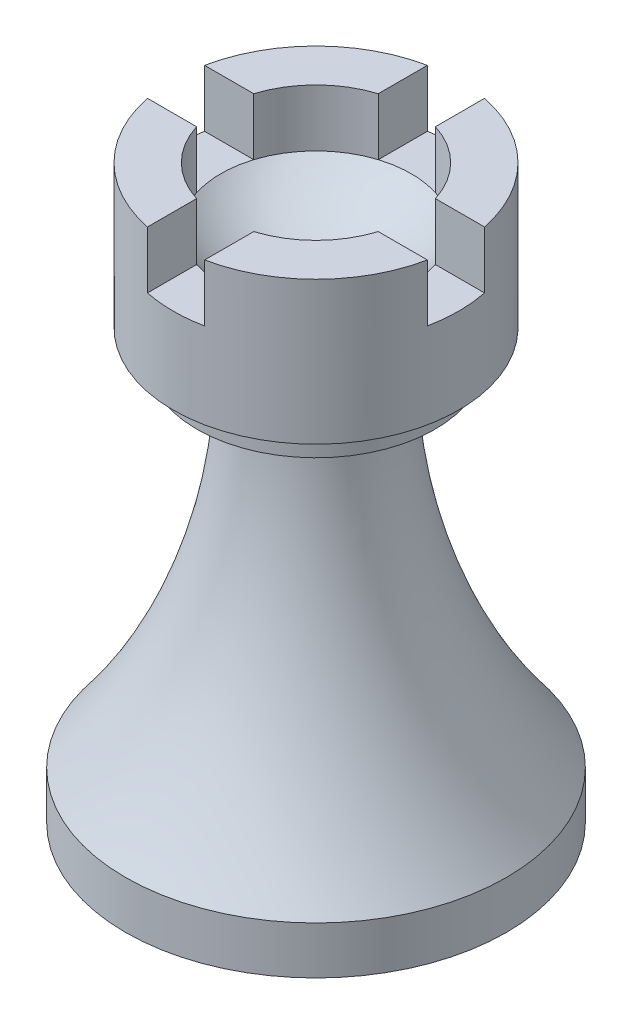
SolidWorks part; units mm, degrees
ref_plane "Front Plane" through (0, 0, 0) normal (0, 0, 1) x (1, 0, 0)
ref_plane "Top Plane" through (0, 0, 0) normal (0, 1, 0) x (1, 0, 0)
ref_plane "Right Plane" through (0, 0, 0) normal (1, 0, 0) x (0, 0, -1)
sketch "Sketch1" plane through (0, 0, 0) normal (0, 0, 1) x (1, 0, 0)
  line L0 (0, 46.6223) -> (0, -55.7864) construction
  line L2 (20, -37) -> (20, -42)
  line L3 (20, -42) -> (0, -42)
  line L4 (7.5, 0) -> (12.5, 0)
  line L5 (12.5, 0) -> (12.5, 3)
  line L6 (12.5, 3) -> (15, 3)
  line L7 (15, 3) -> (15, 18)
  line L8 (15, 18) -> (10, 18)
  line L9 (0, 0) -> (0, 8)
  line L10 (10, 12) -> (10, 18)
  line L11 (10, 3) -> (10, 18) construction
  line L12 (0, 0) -> (0, -42)
  arc A0 (0, 8) -> (10, 12) centre (-0.5956, 23.9889) ccw
  arc A1 (20, -37) -> (7.5, 0) centre (67.499, -0.3415) cw
  point P12 (7.5, 0)
  point P19 (10, 12)
  dimension "D8" = 60
  dimension "D2" = 5
  dimension "D3" = 20
  dimension "D4" = 7.5
  dimension "D5" = 12.5
  dimension "D6" = 3
  dimension "D7" = 15
  dimension "D9" = 10
  dimension "D11" = 6
revolve "Revolve1" add sketch "Sketch1" angle 360 about L0
fillet "Fillet1" radius 2 1 edges at (0, 0, 7.5)
sketch "Sketch2" plane through (0, 0, 0) normal (0, 0, 1) x (1, 0, 0)
  line L0 (10, 18) -> (-10, 18) construction
  line L1 (-3, 24) -> (3, 24)
  line L2 (-3, 24) -> (-3, 12)
  line L3 (-3, 12) -> (3, 12)
  line L4 (3, 24) -> (3, 12)
  line L5 (-3, 24) -> (3, 12) construction
  line L6 (-3, 12) -> (3, 24) construction
  point P0 (0, 18)
  dimension "D1" = 6
  dimension "D2" = 12
extrude "Cut-Extrude1" cut sketch "Sketch2" against normal up to next
pattern_circular "CirPattern1" count 4 over 360 about axis through (0, 0, 0) along (0, 1, 0) of "Cut-Extrude1"
scale "缩放比例1" scale about origin uniform scaling yes scale factor 0.6
